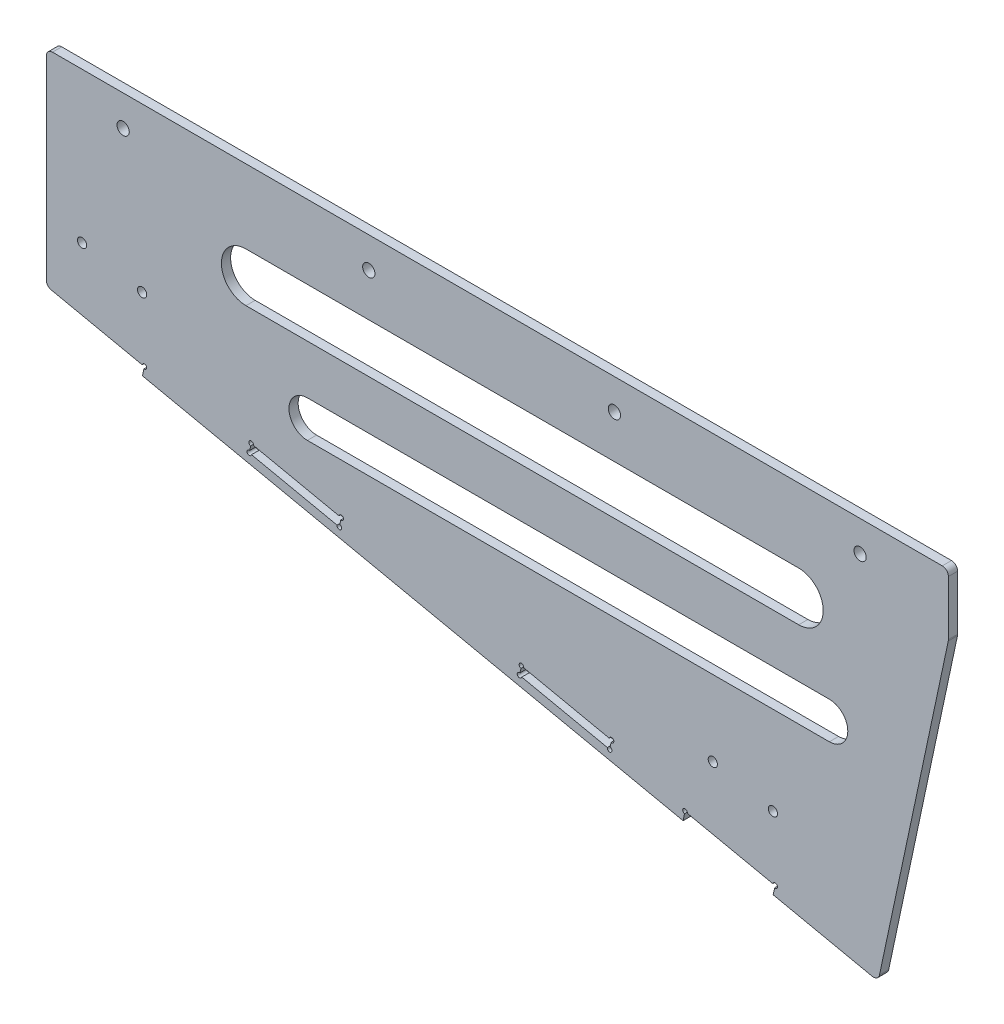
SolidWorks part; units mm, degrees
ref_plane "前视基准面" through (0, 0, 0) normal (0, 0, 1) x (1, 0, 0)
ref_plane "上视基准面" through (0, 0, 0) normal (0, 1, 0) x (1, 0, 0)
ref_plane "右视基准面" through (0, 0, 0) normal (1, 0, 0) x (0, 0, -1)
sketch "草图1" plane through (0, 0, 0) normal (0, 0, 1) x (1, 0, 0)
  line L0 (-31.7701, 71.7677) -> (318.2299, 71.7677)
  line L1 (318.2299, 71.7677) -> (292.9319, -47.2498)
  line L2 (292.9319, -47.2498) -> (-31.7701, 21.7677)
  line L3 (-31.7701, 21.7677) -> (-31.7701, 71.7677)
  dimension "D1" = 78
  dimension "D2" = 350
  dimension "D3" = 50
extrude "凸台-拉伸1" add sketch "草图1" along normal blind 3
sketch "草图3" plane through (0, 0, 3) normal (0, 0, 1) x (1, 0, 0)
  line L0 (-0.4694, 15.1145) -> (0.1544, 18.049)
  line L1 (-31.7701, 21.7677) -> (292.9319, -47.2498) construction
  line L2 (0.1544, 18.049) -> (-31.7701, 24.8347)
  line L3 (-31.7701, 71.7677) -> (-31.7701, 21.7677) construction
  line L4 (-31.7701, 24.8347) -> (-31.7701, 21.7677)
  line L5 (-31.7701, 21.7677) -> (-0.4694, 15.1145)
  line L7 (242.6174, -36.5552) -> (240.1118, -45.9064) construction
  line L8 (240.1118, -45.9064) -> (269.0895, -53.671) construction
  line L9 (269.0895, -53.671) -> (271.5952, -44.3197) construction
  line L10 (271.5952, -44.3197) -> (242.6174, -36.5552) construction
  line L12 (176.2209, -19.3751) -> (205.5654, -25.6125)
  line L13 (175.5972, -22.3096) -> (176.2209, -19.3751)
  line L14 (204.9416, -28.5469) -> (175.5972, -22.3096)
  line L15 (205.5654, -25.6125) -> (204.9416, -28.5469)
  point P1 (-31.7701, 24.334)
  dimension "D2" = 180
  dimension "D3" = 30
  dimension "D1" = 3
  dimension "D4" = 3
  dimension "D5" = 32
extrude "切除-拉伸2" cut sketch "草图3" against normal blind 10
sketch "草图4" plane through (0, 0, 3) normal (0, 0, 1) x (1, 0, 0)
  circle A4 centre (-20.1411, 42.8097) radius 1.5
  circle A5 centre (-0.5781, 38.6515) radius 1.5
  circle A6 centre (185.2699, -0.8517) radius 1.5
  circle A7 centre (204.8328, -5.01) radius 1.5
  dimension "D1" = 3
  dimension "D2" = 3
  dimension "D3" = 3
  dimension "D4" = 3
extrude "切除-拉伸3" cut sketch "草图4" against normal blind 10
sketch "草图7" plane through (0, 0, 3) normal (0, 0, 1) x (1, 0, 0)
  line L0 (292.9319, -47.2498) -> (239.1338, -35.8147)
  line L1 (204.9416, -28.5469) -> (292.9319, -47.2498) construction
  line L2 (239.1338, -35.8147) -> (262.0012, 71.7677)
  line L3 (318.2299, 71.7677) -> (-31.7701, 71.7677) construction
  line L4 (262.0012, 71.7677) -> (318.2299, 71.7677)
  line L5 (318.2299, 71.7677) -> (292.9319, -47.2498)
  dimension "D1" = 55
extrude "切除-拉伸6" cut sketch "草图7" against normal through all
sketch "草图8" plane through (0, 0, 3) normal (0, 0, 1) x (1, 0, 0)
  circle A0 centre (182.503, -9.7647) radius 1.5
  circle A1 centre (201.8215, -14.9411) radius 1.5
  dimension "D1" = 3
  dimension "D2" = 3
extrude "切除-拉伸7" [suppressed] cut sketch "草图8" against normal through all
sketch "草图12" plane through (0, 0, 3) normal (0, 0, 1) x (1, 0, 0)
  line L0 (-31.7701, 71.7677) -> (-31.7701, 91.7677)
  line L1 (-31.7701, 91.7677) -> (262.0012, 91.7677)
  line L2 (262.0012, 91.7677) -> (262.0012, 71.7677)
  line L3 (262.0012, 71.7677) -> (-31.7701, 71.7677)
  dimension "D1" = 90
  dimension "D2" = 20
extrude "凸台-拉伸2" add sketch "草图12" against normal blind 3
sketch "草图13" plane through (0, 0, 3) normal (0, 0, 1) x (1, 0, 0)
  line L0 (262.0012, 91.7677) -> (-31.7701, 91.7677) construction
  line L1 (-31.7701, 91.7677) -> (-31.7701, 24.8347) construction
  circle A0 centre (-6.7701, 81.7677) radius 2
  circle A1 centre (73.2299, 81.7677) radius 2
  circle A2 centre (153.2299, 81.7677) radius 2
  circle A3 centre (233.2299, 81.7677) radius 2
  dimension "D1" = 80
  dimension "D2" = 80
  dimension "D3" = 80
  dimension "D4" = 4
  dimension "D5" = 10
  dimension "D6" = 10
  dimension "D7" = 10
  dimension "D8" = 10
  dimension "D9" = 25
  dimension "D10" = 4
  dimension "D11" = 4
  dimension "D12" = 4
extrude "切除-拉伸9" cut sketch "草图13" against normal through all
sketch "草图14" plane through (0, 0, 3) normal (0, 0, 1) x (1, 0, 0)
  line L0 (33.2299, 59.7677) -> (213.2299, 59.7677) construction
  line L1 (33.2299, 67.7677) -> (213.2299, 67.7677)
  line L2 (33.2299, 51.7677) -> (213.2299, 51.7677)
  line L3 (262.0012, 91.7677) -> (-31.7701, 91.7677) construction
  line L4 (-31.7701, 91.7677) -> (-31.7701, 24.8347) construction
  line L5 (53.2299, 29.7677) -> (223.2299, 29.7677) construction
  line L6 (53.2299, 35.7677) -> (223.2299, 35.7677)
  line L7 (53.2299, 23.7677) -> (223.2299, 23.7677)
  arc A0 (33.2299, 67.7677) -> (33.2299, 51.7677) centre (33.2299, 59.7677) ccw
  arc A1 (213.2299, 51.7677) -> (213.2299, 67.7677) centre (213.2299, 59.7677) ccw
  arc A2 (53.2299, 35.7677) -> (53.2299, 23.7677) centre (53.2299, 29.7677) ccw
  arc A3 (223.2299, 23.7677) -> (223.2299, 35.7677) centre (223.2299, 29.7677) ccw
  point P2 (123.2299, 59.7677)
  point P13 (138.2299, 29.7677)
  point P18 (163.5277, 29.7677)
  point P19 (53.8356, 29.7677)
  point P20 (193.7297, 29.7677)
  point P21 (219.1479, 29.7677)
  point P22 (19.4201, 29.7677)
  point P23 (231.7889, 34.7677)
  point P24 (222.3393, 34.7677)
  point P25 (53.986, 34.7677)
  dimension "D1" = 16
  dimension "D2" = 24
  dimension "D3" = 65
  dimension "D4" = 180
  dimension "D5" = 12
  dimension "D6" = 30
  dimension "D7" = 20
  dimension "D8" = 10
extrude "切除-拉伸10" cut sketch "草图14" against normal blind 10
hole_wizard "大小mm 暗销槽口2" positions "草图16" profile "草图17" size "Ø1.5" standard "GB" slot yes end condition through all
sketch "草图16" plane through (0, 0, 3) normal (0, 0, 1) x (1, 0, 0)
  point P0 (0.1544, 18.049)
  point P3 (176.2209, -19.3751)
  point P6 (205.5654, -25.6125)
sketch "草图17" plane through (0.1544, 18.049, 3) normal (1, 0, 0) x (0, -1, 0)
  line L0 (0, 0) -> (0, 3)
  line L1 (0, 3) -> (0.75, 3)
  line L2 (0.75, 3) -> (0.75, 0)
  line L5 (0.75, 0) -> (0, 0)
  line L11 (0, -6.35) -> (0, 107.95) construction
  dimension "通孔孔直径" = 1.5
  dimension "通孔孔深度" = 3
sketch "草图18" plane through (0, 0, 0) normal (0, 0, -1) x (-1, 0, 0)
  line L0 (-152.2916, -11.2218) -> (-151.6679, -14.1562)
  line L1 (-151.6679, -14.1562) -> (-122.3235, -7.9189)
  line L2 (-122.3235, -7.9189) -> (-122.9472, -4.9844)
  line L3 (-122.9472, -4.9844) -> (-152.2916, -11.2218)
  line L4 (-64.2584, 7.4903) -> (-63.6346, 4.5558)
  line L5 (-63.6346, 4.5558) -> (-34.2902, 10.7932)
  line L6 (-34.2902, 10.7932) -> (-34.9139, 13.7276)
  line L7 (-34.9139, 13.7276) -> (-64.2584, 7.4903)
  point P8 (-151.6679, -14.1562)
extrude "切除-拉伸11" cut sketch "草图18" against normal through all
hole_wizard "大小mm 暗销槽口3" positions "草图19" profile "草图20" size "Ø1.5" standard "GB" slot yes end condition through all
sketch "草图19" plane through (0, 0, 0) normal (0, 0, -1) x (-1, 0, 0)
  line L0 (-151.6679, -14.1562) -> (-122.3235, -7.9189) construction
  line L1 (-152.2916, -11.2218) -> (-151.6679, -14.1562) construction
  point P0 (-152.2916, -11.2218)
  point P3 (-151.6679, -14.1562)
  point P9 (-122.3235, -7.9189)
  point P12 (-122.9472, -4.9844)
  point P15 (-64.2584, 7.4903)
  point P18 (-63.6346, 4.5558)
  point P21 (-34.2902, 10.7932)
  point P24 (-34.9139, 13.7276)
sketch "草图20" plane through (152.2916, -11.2218, 0) normal (1, 0, 0) x (0, 1, 0)
  line L0 (0, 0) -> (0, 3)
  line L1 (0, 3) -> (0.75, 3)
  line L2 (0.75, 3) -> (0.75, 0)
  line L5 (0.75, 0) -> (0, 0)
  line L11 (0, -6.35) -> (0, 107.95) construction
  dimension "通孔孔直径" = 1.5
  dimension "通孔孔深度" = 3
fillet "圆角1" radius 2 5 edges at (-31.7701, 91.7677, 1.5) (-31.7701, 24.8347, 1.5) (239.1338, -35.8147, 1.5) (262.0012, 71.7677, 1.5) (262.0012, 91.7677, 1.5)
